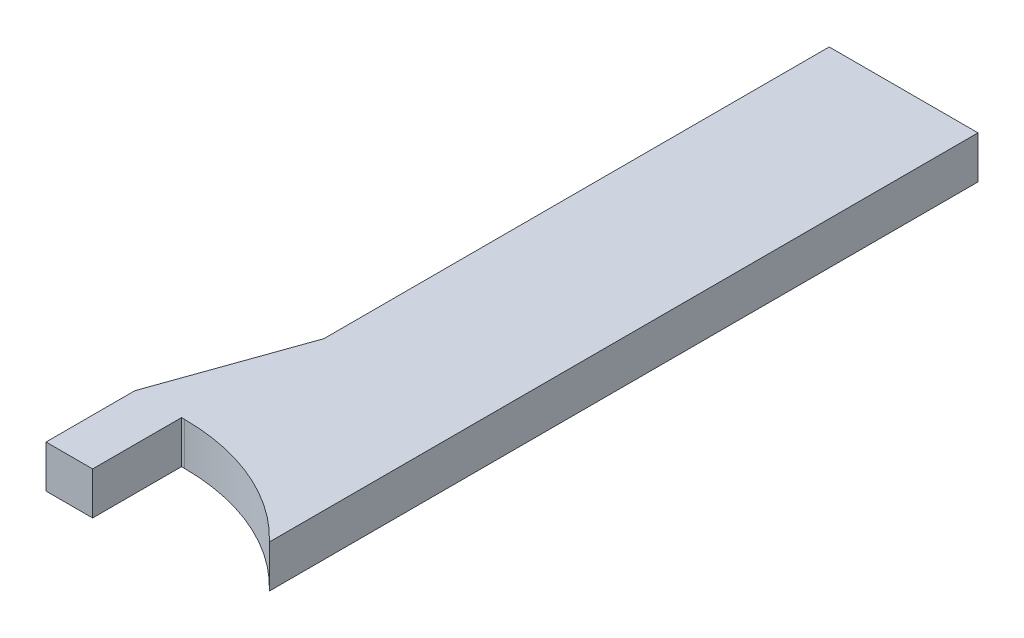
SolidWorks part; units mm, degrees
ref_plane "前视基准面" through (0, 0, 0) normal (0, 0, 1) x (1, 0, 0)
ref_plane "上视基准面" through (0, 0, 0) normal (0, 1, 0) x (1, 0, 0)
ref_plane "右视基准面" through (0, 0, 0) normal (1, 0, 0) x (0, 0, -1)
other "Configuration Table"
sketch "草图1" plane through (0, 0, 0) normal (0, 1, 0) x (1, 0, 0)
  line L0 (0, 0) -> (14.5, 0)
  line L1 (0, 0) -> (0, 14.5)
  line L2 (0, 10) -> (10.5, 10)
  line L3 (10.5, 10) -> (10.5, 31.7618)
  line L4 (10.5, 31.7618) -> (0, 31.7618)
  line L5 (0, 31.7618) -> (0, 14.3623)
  arc A0 (14.5, 0) -> (0, 14.5) centre (0, 0) ccw
  dimension "D1" = 14.5
  dimension "D2" = 10
extrude "凸台-拉伸1" add sketch "草图1" along normal blind 3 contours A0 L3 L4 L5
sketch "草图2" plane through (0, 3, 0) normal (0, 1, 0) x (1, 0, 0)
  line L0 (0, 14.5) -> (-3.489, 14.5)
  line L1 (-3.489, 14.5) -> (-3.489, 8.2279)
  line L2 (-3.489, 8.2279) -> (-0.2, 8.2279)
  line L3 (-0.2, 8.2279) -> (-0.2, 14.5)
  line L4 (-3.489, 14.5) -> (0, 24.3472)
  line L5 (0, 31.7618) -> (0, 14.5) construction
  line L6 (0, 24.3472) -> (0, 14.5)
  line M7 (0, 31.7618) -> (0, 14.5)
  dimension "D1" = 0.2
extrude "凸台-拉伸2" add sketch "草图2" against normal blind 3 contours L4 L0 M7 | L2 L3 L0 L1
sketch "草图3" plane through (0, 3, 0) normal (0, 1, 0) x (1, 0, 0)
  line L0 (10.5, 10) -> (10.5, 31.7618) construction
  line L2 (0, 31.7618) -> (10.5, 31.7618)
  line L3 (0, 31.7618) -> (0, 60)
  line L4 (0, 60) -> (10.5, 60)
  line L5 (10.5, 31.7618) -> (10.5, 60)
  dimension "D1" = 50
extrude "凸台-拉伸3" add sketch "草图3" against normal up to surface (3 mm away) up to face at (1.5649, 0, -17.656)
